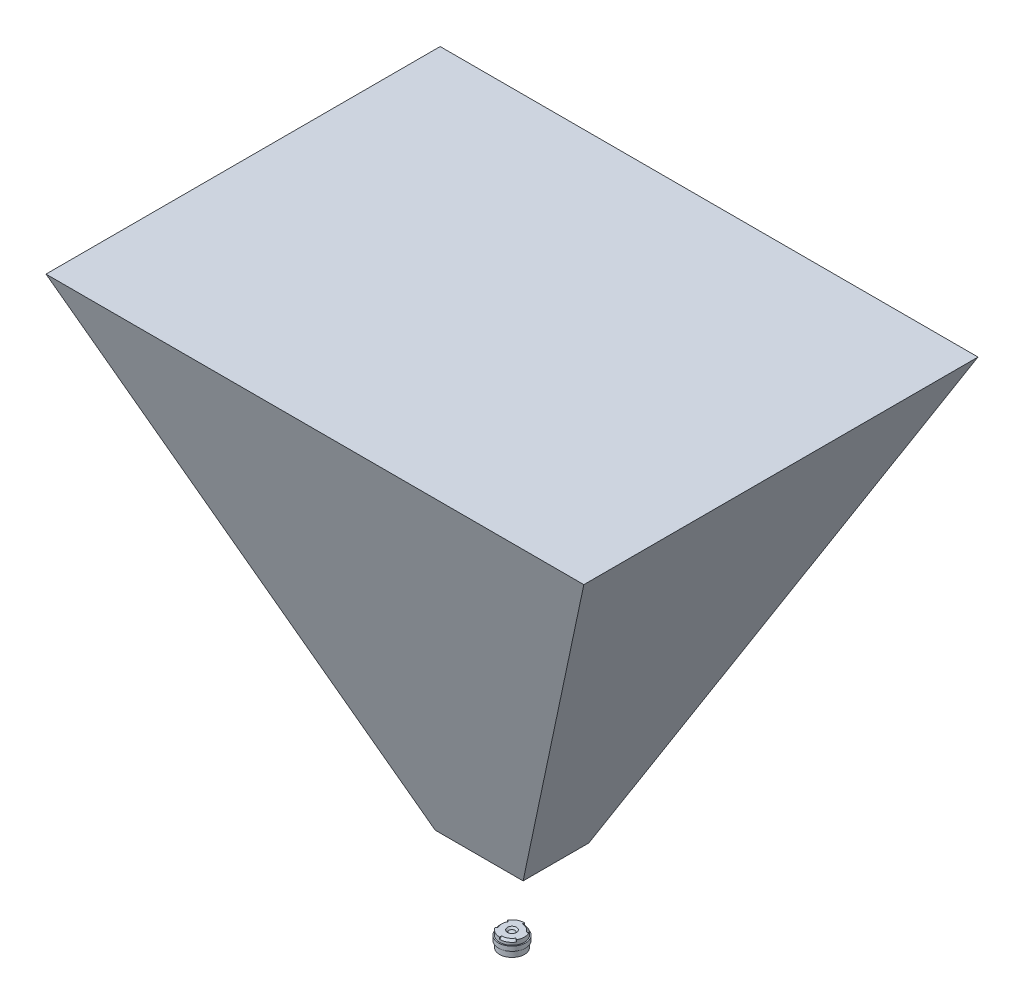
SolidWorks part; units mm, degrees
material "ABS PC"
ref_plane "Vorne" through (0, 0, 0) normal (0, 0, 1) x (1, 0, 0)
ref_plane "Oben" through (0, 0, 0) normal (0, 1, 0) x (1, 0, 0)
ref_plane "Rechts" through (0, 0, 0) normal (1, 0, 0) x (0, 0, -1)
sketch "Skizze3" plane through (0, 0, 0) normal (0, 0, 1) x (1, 0, 0)
  line L0 (0, 0) -> (0, -2.1568) construction
  line L1 (1, 0.8) -> (2.75, 0.8)
  line L2 (2.75, 0.8) -> (2.75, -2.55)
  line L3 (2.75, -2.55) -> (2.1, -2.55)
  line L4 (1, 0.8) -> (0.625, 0.425)
  line L5 (0.8125, 0.6125) -> (0.8125, 0.8) construction
  line L6 (0.8125, 0.8) -> (1, 0.8) construction
  line L7 (2.1, -2.55) -> (1.8, -2.25)
  line L8 (2.1, -2.55) -> (2.1, -2.4) construction
  line L9 (2.1, -2.4) -> (1.95, -2.4) construction
  line L10 (0, -2.55) -> (0, 0.525)
  arc A0 (1.8, -2.25) -> (0, -2.55) centre (0, 3) cw
  arc A1 (0, 0.525) -> (0.625, 0.425) centre (0, -1.4781) cw
  dimension "D6" = 0.1
  dimension "D1" = 3.35
  dimension "D2" = 5.5
  dimension "D3" = 2
  dimension "D4" = 1.25
  dimension "D5" = 3.6
  dimension "D7" = 0.8
  dimension "D8" = 0.3
revolve "Body" add sketch "Skizze3" angle 360 about L0
sketch "Skizze4" plane through (0, 0, 0) normal (0, 0, 1) x (1, 0, 0)
  line L0 (0, 0) -> (0, 1.3093) construction
  line L1 (2.75, -2.55) -> (2.75, 0.8) construction
  line L2 (2.75, -0.2) -> (3, -0.2)
  line L3 (2.75, -0.2) -> (2.75, -1.2)
  line L4 (2.75, -1.2) -> (3, -1.2)
  line L5 (3, -0.2) -> (3, -1.2)
  line L6 (2.75, 0.8) -> (-2.75, 0.8) construction
  dimension "D1" = 2
  dimension "D2" = 1
  dimension "D3" = 6
revolve "Thread" add sketch "Skizze4" angle 360 about L0
sketch "Skizze5" plane through (0, 0, 0) normal (1, 0, 0) x (0, 0, -1)
  line L0 (0, 0) -> (0, -3.7681) construction
  line L1 (2.75, 0.8) -> (2.75, 0.35)
  line L2 (2.75, -0.2) -> (2.75, 0.8) construction
  line L3 (2.75, 0.35) -> (2.3, 0.8)
  line L4 (2.75, 0.8) -> (-2.75, 0.8) construction
  line L5 (2.3, 0.8) -> (2.75, 0.8)
  dimension "D1" = 0.45
revolve "Toolface" cut sketch "Skizze5" angle 60 about L0
pattern_circular "Kreismuster1" count 3 over 360 about axis through (0, 0, 0) along (0, 1, 0) of "Toolface"
sketch "Skizze6" plane through (0, 0, 0) normal (1, 0, 0) x (0, 0, -1)
  line L0 (0, 0) -> (0, 10.2784) construction
  line L1 (-7.2794, 18.7078) -> (-43.6764, 118.7078)
  line L2 (-43.6764, 118.7078) -> (43.6764, 118.7078)
  line L3 (-7.2794, 18.7078) -> (7.2794, 18.7078)
  line L4 (0, 118.7078) -> (0, 18.7078) construction
  line L5 (-7.2794, 18.7078) -> (0, -1.2922) construction
  line L8 (7.2794, 18.7078) -> (43.6764, 118.7078)
  point P3 (-0.625, 0.425)
  dimension "D1" = 100
  dimension "D2" = 20
  dimension "D3" = 40
extrude "FOV - 3,6mm f/2,9" add sketch "Skizze6" along normal mid plane 200 separate body
sketch "Skizze8" plane through (0, 0, 0) normal (0, 0, 1) x (1, 0, 0)
  line L0 (0, 0) -> (0, 233.3089) construction
  line L1 (-9.7405, 18.7078) -> (-59.5986, 118.7078)
  line L2 (100, 18.7078) -> (-100, 18.7078) construction
  line L3 (100, 118.7078) -> (-100, 118.7078) construction
  line L4 (-59.5986, 118.7078) -> (59.5986, 118.7078)
  line L5 (-9.7405, 18.7078) -> (9.7405, 18.7078)
  line L8 (9.7405, 18.7078) -> (59.5986, 118.7078)
  circle A0 centre (0, 0) radius 5
  point P9 (-0.625, 0.425)
  point P16 (0, 18.7078)
  point P17 (0, 118.7078)
  dimension "D2" = 10
  dimension "D1" = 53
extrude "FOV2" cut sketch "Skizze8" against normal through all and the other way through all flip side to cut
